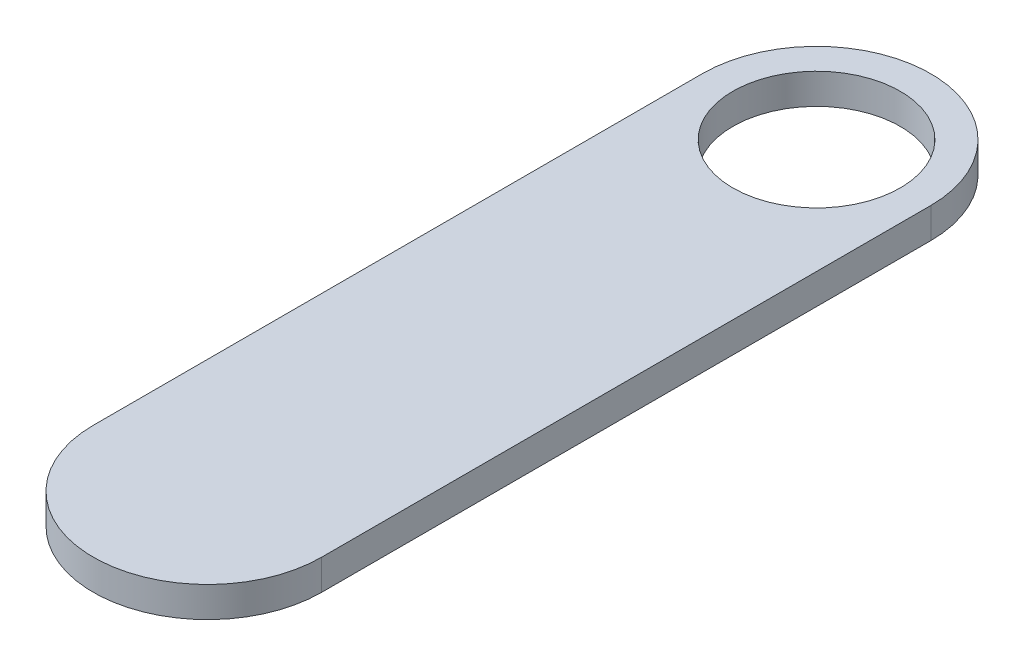
SolidWorks part; units mm, degrees
ref_plane "Front Plane" through (0, 0, 0) normal (0, 0, 1) x (1, 0, 0)
ref_plane "Top Plane" through (0, 0, 0) normal (0, 1, 0) x (1, 0, 0)
ref_plane "Right Plane" through (0, 0, 0) normal (1, 0, 0) x (0, 0, -1)
sketch "Sketch2" plane through (0, 0, 0) normal (0, 1, 0) x (1, 0, 0)
  line L0 (0, 0) -> (0, 40) construction
  line L1 (-7.5, 0) -> (-7.5, 40)
  line L2 (7.5, 0) -> (7.5, 40)
  arc A0 (-7.5, 0) -> (7.5, 0) centre (0, 0) ccw
  arc A1 (7.5, 40) -> (-7.5, 40) centre (0, 40) ccw
  circle A2 centre (0, 40) radius 5.5
  point P3 (0, 20)
  dimension "D3" = 11
  dimension "D1" = 15
  dimension "D2" = 40
extrude "Boss-Extrude1" add sketch "Sketch2" along normal blind 2
